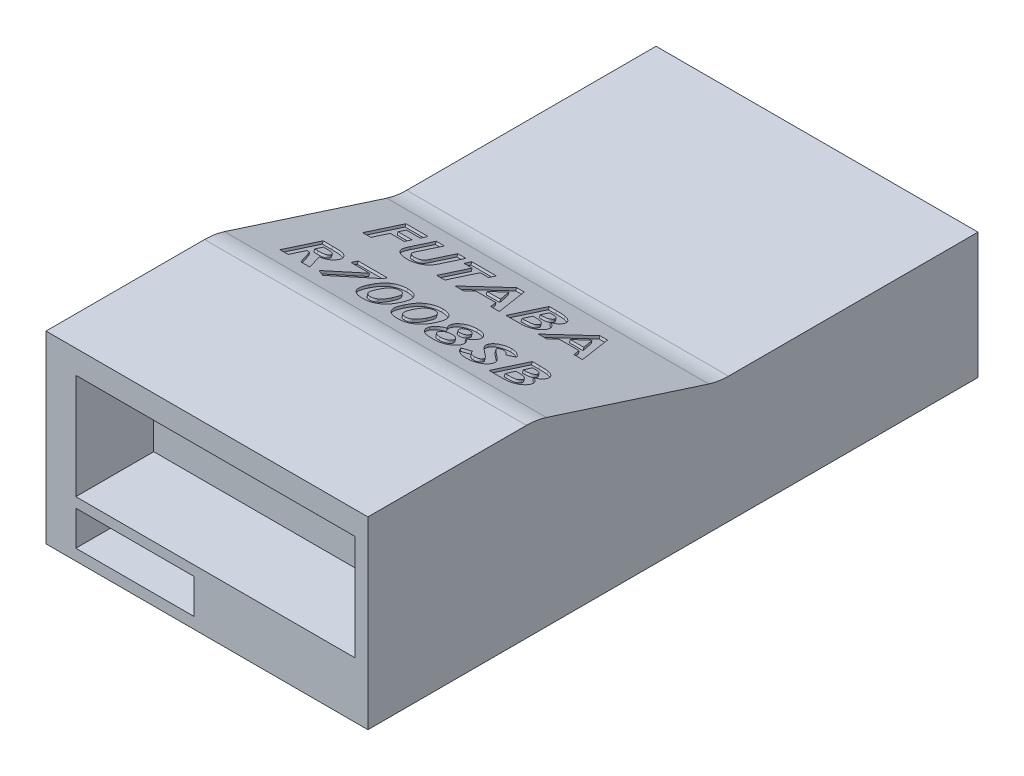
SolidWorks part; units mm, degrees
ref_plane "前视基准面" through (0, 0, 0) normal (0, 0, 1) x (1, 0, 0)
ref_plane "上视基准面" through (0, 0, 0) normal (0, 1, 0) x (1, 0, 0)
ref_plane "右视基准面" through (0, 0, 0) normal (1, 0, 0) x (0, 0, -1)
sketch "草图1" plane through (0, 0, 0) normal (1, 0, 0) x (0, 0, -1)
  line L0 (0, 0) -> (47, 0)
  line L1 (47, 0) -> (47, 9.7)
  line L2 (47, 9.7) -> (27.7838, 9.7)
  line L3 (26.2538, 9.9399) -> (13.7462, 13.9601)
  line L4 (12.2162, 14.2) -> (0, 14.2)
  line L5 (0, 14.2) -> (0, 0)
  arc A0 (12.2162, 14.2) -> (13.7462, 13.9601) centre (12.2162, 9.2) cw
  arc A1 (27.7838, 9.7) -> (26.2538, 9.9399) centre (27.7838, 14.7) cw
  point P9 (13, 14.2)
  point P12 (27, 9.7)
  dimension "D6" = 5
  dimension "D7" = 5
  dimension "D1" = 14.2
  dimension "D2" = 9.7
  dimension "D3" = 47
  dimension "D4" = 13
  dimension "D5" = 20
extrude "凸台-拉伸1" add sketch "草图1" along normal mid plane 24.8
sketch "草图2" plane through (0, 0, 0) normal (0, 0, 1) x (1, 0, 0)
  line L0 (12.4, 14.2) -> (-12.4, 14.2) construction
  line L1 (-10.1, 12.4) -> (11.4, 12.4)
  line L2 (-10.1, 12.4) -> (-10.1, 4.3)
  line L3 (-10.1, 4.3) -> (11.4, 4.3)
  line L4 (11.4, 12.4) -> (11.4, 4.3)
  line L5 (-10.1, 12.4) -> (11.4, 4.3) construction
  line L6 (-10.1, 4.3) -> (11.4, 12.4) construction
  line L7 (12.4, 14.2) -> (12.4, 0) construction
  line L8 (-12.4, 14.2) -> (-12.4, 0) construction
  line L9 (12.4, 0) -> (-12.4, 0) construction
  line L11 (-10.1, 3.53) -> (-1, 3.53)
  line L12 (-10.1, 3.53) -> (-10.1, 0.86)
  line L13 (-10.1, 0.86) -> (-1, 0.86)
  line L14 (-1, 3.53) -> (-1, 0.86)
  line L15 (-10.1, 3.53) -> (-1, 0.86) construction
  line L16 (-10.1, 0.86) -> (-1, 3.53) construction
  point P0 (0.65, 8.35)
  point P13 (-5.55, 2.195)
  dimension "D1" = 1.8
  dimension "D2" = 1
  dimension "D3" = 2.3
  dimension "D4" = 4.3
  dimension "D5" = 2.3
  dimension "D6" = 9.1
  dimension "D7" = 0.77
  dimension "D8" = 0.86
extrude "切除-拉伸1" cut sketch "草图2" against normal blind 6
sketch "草图3" plane through (0, 0, -47) normal (0, 0, -1) x (-1, 0, 0)
  line L0 (12.4, 0) -> (12.4, 9.7) construction
  line L1 (-12.4, 9.7) -> (12.4, 9.7) construction
  circle A0 centre (7.4, 6.9) radius 1.25
  circle A1 centre (1.4, 6.9) radius 1.25
  dimension "D1" = 2.5
  dimension "D2" = 2.5
  dimension "D3" = 5
  dimension "D4" = 6
  dimension "D5" = 2.8
extrude "凸台-拉伸2" add sketch "草图3" along normal blind 0.2
sketch "草图4" plane through (0, 16.6576, -5.3542) normal (0, 0.952, -0.306) x (1, 0, 0)
  line L0 (12.4, 21.9527) -> (-12.4, 21.9527) construction
  line L1 (-12.4, 21.9527) -> (-12.4, 8.8149) construction
  text T0 "<b>FUTABA</b>\r\n<b>R7008SB</b>"
  dimension "D1" = 5
  dimension "D2" = 2.5
extrude "切除-拉伸2" cut sketch "草图4" against normal blind 0.2
